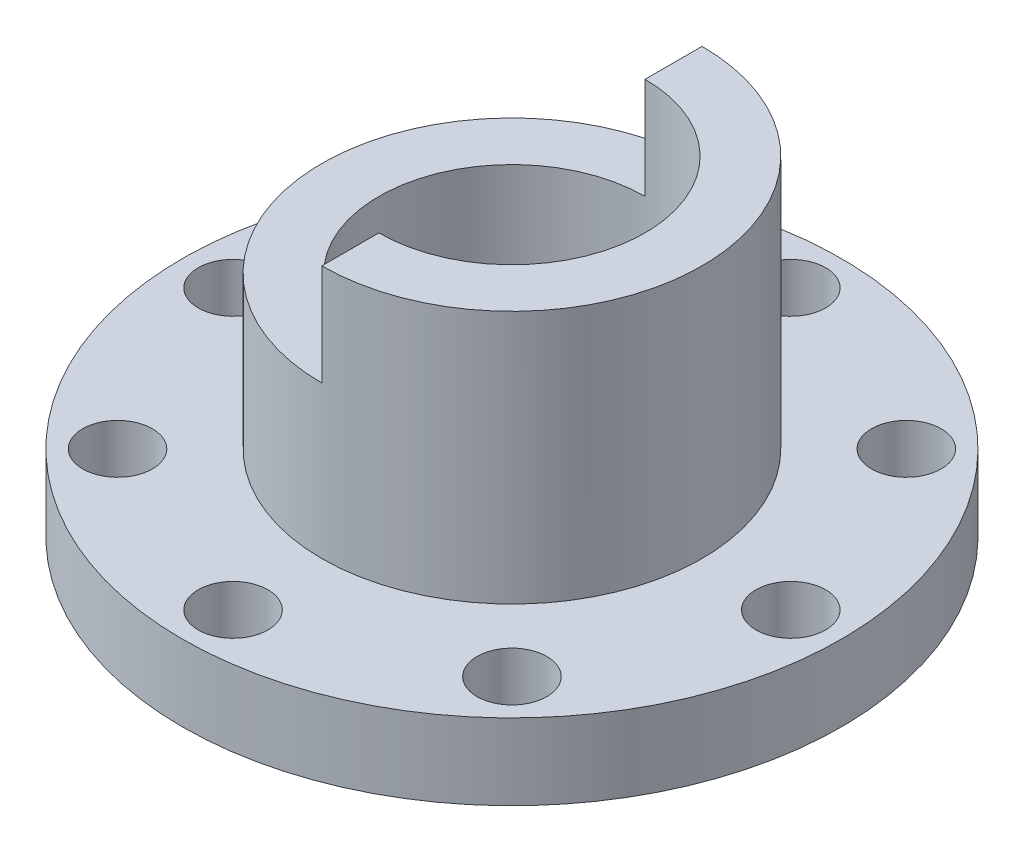
SolidWorks part; units mm, degrees
ref_plane "Front Plane" through (0, 0, 0) normal (0, 0, 1) x (1, 0, 0)
ref_plane "Top Plane" through (0, 0, 0) normal (0, 1, 0) x (1, 0, 0)
ref_plane "Right Plane" through (0, 0, 0) normal (1, 0, 0) x (0, 0, -1)
sketch "Sketch1" plane through (0, 0, 0) normal (0, 1, 0) x (1, 0, 0)
  circle A0 centre (0, 0) radius 11
  circle A1 centre (0, 11) radius 1.375
  circle A2 centre (7.7782, 7.7782) radius 1.375
  circle A3 centre (11, 0) radius 1.375
  circle A4 centre (7.7782, -7.7782) radius 1.375
  circle A5 centre (0, -11) radius 1.375
  circle A6 centre (-7.7782, -7.7782) radius 1.375
  circle A7 centre (-11, 0) radius 1.375
  circle A8 centre (-7.7782, 7.7782) radius 1.375
  circle A9 centre (0, 0) radius 13
  circle A10 centre (0, 0) radius 5
  point P21 (0, 0)
  dimension "D1" = 22
  dimension "D2" = 2.75
  dimension "D4" = 26
  dimension "D5" = 10
  dimension "D3" = 8
extrude "Boss-Extrude1" add sketch "Sketch1" along normal blind 3 contours A8 A0 A7 A6 A5 A4 A3 A2 A1 A10 | A9 A8 A0 A1 A2 A3 A4 A5 A6 A7
sketch "Sketch2" plane through (0, 3, 0) normal (0, 1, 0) x (1, 0, 0)
  circle A0 centre (0, 0) radius 5
  circle A1 centre (0, 0) radius 7.5
  dimension "D1" = 15
extrude "Boss-Extrude2" add sketch "Sketch2" along normal blind 10
sketch "Sketch3" plane through (0, 13, 0) normal (0, 1, 0) x (1, 0, 0)
  circle A0 centre (0, 0) radius 5.25
  dimension "D1" = 10.5
extrude "Cut-Extrude1" cut sketch "Sketch3" against normal blind 18
sketch "Sketch4" plane through (0, 13, 0) normal (0, 1, 0) x (1, 0, 0)
  line L0 (0, 7.5) -> (0, -7.5)
  circle A0 centre (0, 0) radius 7.5
  circle M1 centre (0, 0) radius 5.25
  circle M2 centre (0, 0) radius 7.5
extrude "Cut-Extrude2" cut sketch "Sketch4" against normal blind 4 contours L0 M2 M1
sketch "Sketch5" plane through (0, 13, 0) normal (0, 1, 0) x (1, 0, 0)
  circle A0 centre (0, 0) radius 7.5
  circle A1 centre (0, 0) radius 7.45
  dimension "D1" = 14.9
extrude "Cut-Extrude3" cut sketch "Sketch5" against normal blind 10
sketch "Sketch6" plane through (0, 9, 0) normal (0, 1, 0) x (1, 0, 0)
  circle A0 centre (0, 0) radius 7.5
  circle A1 centre (0, 0) radius 5.25
  dimension "D1" = 15
extrude "Boss-Extrude3" add sketch "Sketch6" against normal blind 6
sketch "Sketch7" plane through (0, 9, 0) normal (0, 1, 0) x (1, 0, 0)
  line L0 (0, 7.5) -> (0, -7.5)
  circle A0 centre (0, 0) radius 7.5
  circle A1 centre (0, 0) radius 7.45
  arc M3 (0, 7.45) -> (0, -7.45) centre (0, 0) cw
  circle M6 centre (0, 0) radius 7.5
extrude "Boss-Extrude4" add sketch "Sketch7" along normal blind 4 contours L0 M6 M3
